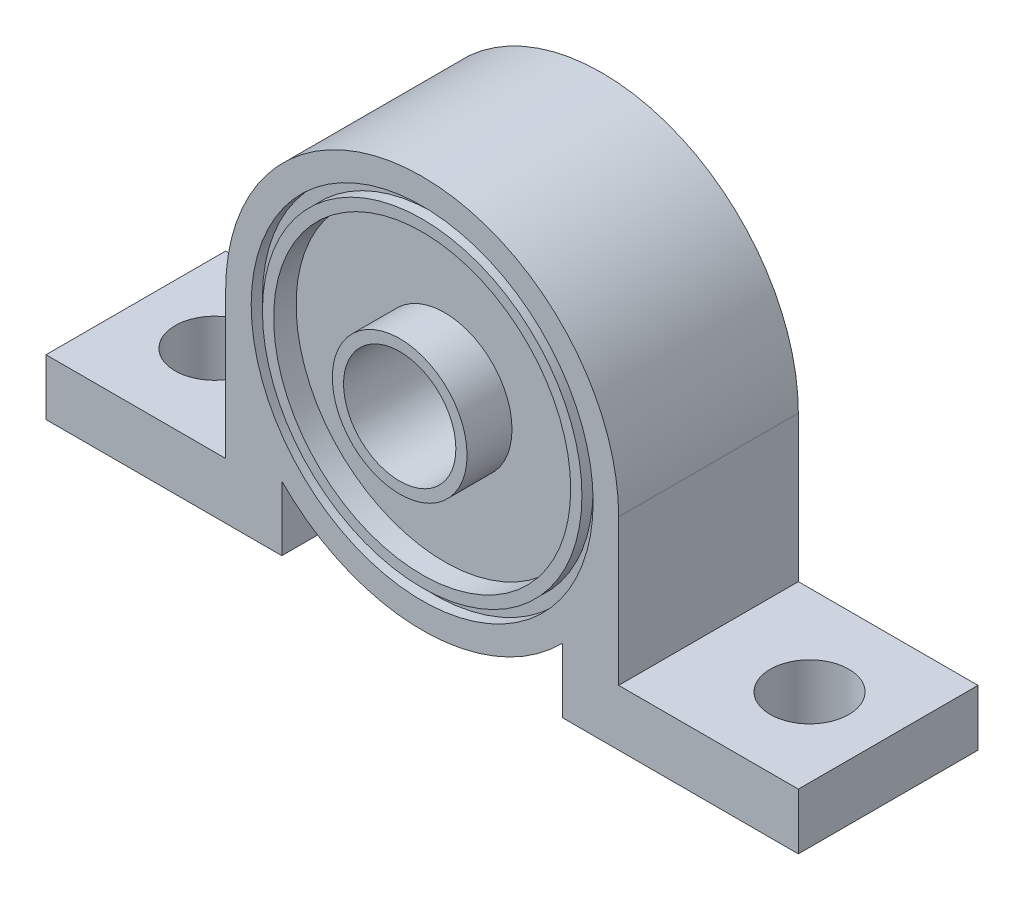
SolidWorks part; units mm, degrees
ref_plane "前视基准面" through (0, 0, 0) normal (0, 0, 1) x (1, 0, 0)
ref_plane "上视基准面" through (0, 0, 0) normal (0, 1, 0) x (1, 0, 0)
ref_plane "右视基准面" through (0, 0, 0) normal (1, 0, 0) x (0, 0, -1)
sketch "草图1" plane through (0, 0, 0) normal (0, 0, 1) x (1, 0, 0)
  line L0 (-12.5, -18) -> (-33.5, -18)
  line L1 (-33.5, -18) -> (-33.5, -13)
  line L2 (-33.5, -13) -> (-17.5, -13)
  line L3 (-17.5, -13) -> (-17.5, 0)
  line L4 (-12.5, -18) -> (-12.5, -12.2474)
  line L5 (0, 21.1256) -> (0, -23.2006) construction
  line L6 (12.5, -18) -> (12.5, -12.2474)
  line L7 (17.5, -13) -> (17.5, 0)
  line L8 (33.5, -13) -> (17.5, -13)
  line L9 (33.5, -18) -> (33.5, -13)
  line L10 (12.5, -18) -> (33.5, -18)
  circle A0 centre (0, 0) radius 5
  arc A1 (17.5, 0) -> (-17.5, 0) centre (0, 0) ccw
  arc A2 (-12.5, -12.2474) -> (12.5, -12.2474) centre (0, 0) ccw
  dimension "D1" = 10
  dimension "D2" = 35
  dimension "D3" = 5
  dimension "D4" = 67
  dimension "D5" = 5
  dimension "D6" = 18
extrude "凸台-拉伸1" add sketch "草图1" along normal blind 16
sketch "草图2" plane through (0, 0, 16) normal (0, 0, 1) x (1, 0, 0)
  circle A0 centre (0, 0) radius 5
  circle A1 centre (0, 0) radius 6
  dimension "D1" = 1
extrude "凸台-拉伸2" add sketch "草图2" along normal blind 2
sketch "草图3" plane through (0, 0, 16) normal (0, 0, 1) x (1, 0, 0)
  circle A0 centre (0, 0) radius 6
  circle A1 centre (0, 0) radius 13.2271
extrude "切除-拉伸1" cut sketch "草图3" against normal blind 2
sketch "草图4" plane through (0, 0, 0) normal (0, 0, -1) x (-1, 0, 0)
  circle A0 centre (0, 0) radius 6
  circle A1 centre (0, 0) radius 5 construction
  circle A2 centre (0, 0) radius 13.4024
  dimension "D1" = 1
extrude "切除-拉伸2" cut sketch "草图4" against normal blind 2
sketch "草图5" plane through (0, 0, 16) normal (0, 0, 1) x (1, 0, 0)
  circle A0 centre (0, 0) radius 14.2271
  circle A1 centre (0, 0) radius 15.2271
  circle A2 centre (0, 0) radius 13.2271 construction
  dimension "D1" = 1
  dimension "D2" = 1
extrude "切除-拉伸3" cut sketch "草图5" against normal blind 1
sketch "草图6" plane through (0, -18, 0) normal (0, -1, 0) x (1, 0, 0)
  line L0 (-33.5, 8) -> (46.4125, 8) construction
  line L1 (-33.5, 16) -> (-33.5, 0) construction
  line L2 (0, 18) -> (0, -8.6709) construction
  line L3 (5, 18) -> (-5, 18) construction
  circle A0 centre (26.5, 8) radius 3.5
  circle A1 centre (-26.5, 8) radius 3.5
  dimension "D1" = 7
  dimension "D2" = 53
extrude "切除-拉伸4" cut sketch "草图6" against normal blind 10
